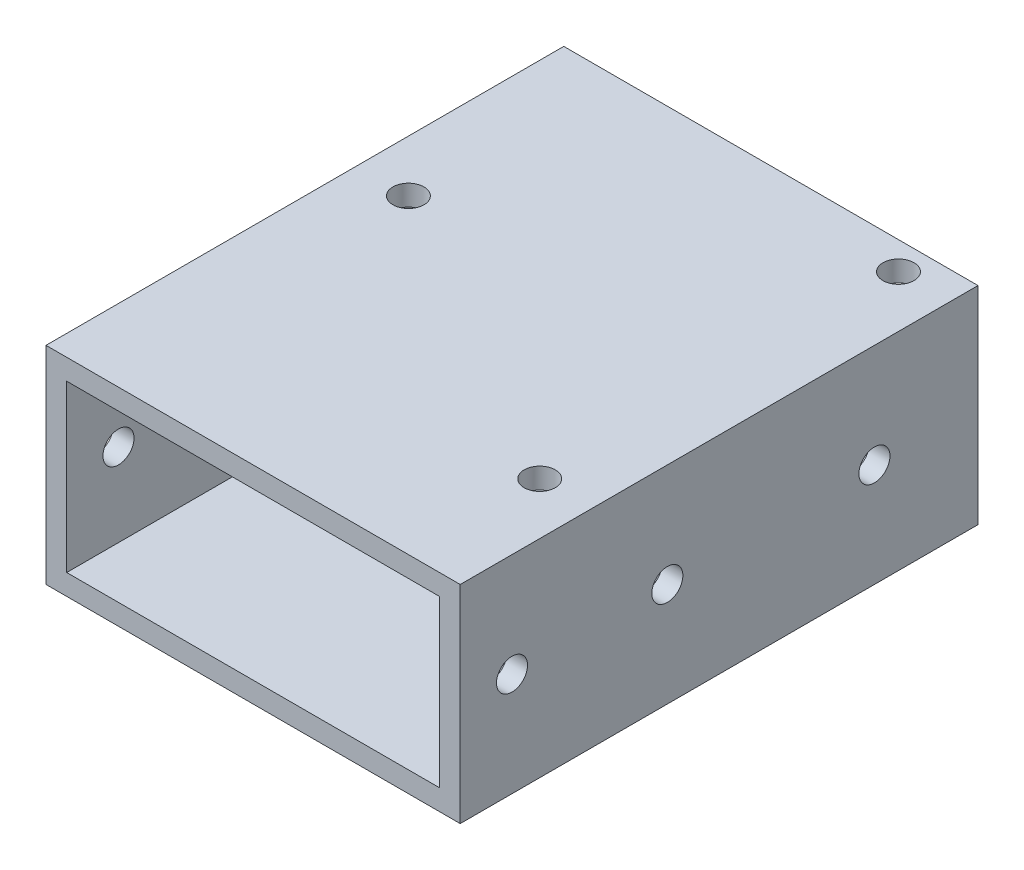
SolidWorks part; units mm, degrees
ref_plane "前视基准面" through (0, 0, 0) normal (0, 0, 1) x (1, 0, 0)
ref_plane "上视基准面" through (0, 0, 0) normal (0, 1, 0) x (1, 0, 0)
ref_plane "右视基准面" through (0, 0, 0) normal (1, 0, 0) x (0, 0, -1)
other "Configuration Table"
sketch "草图1" plane through (0, 0, 0) normal (0, 0, 1) x (1, 0, 0)
  line L1 (-20, 10) -> (20, 10)
  line L2 (-20, 10) -> (-20, -10)
  line L3 (-20, -10) -> (20, -10)
  line L4 (20, 10) -> (20, -10)
  line L5 (-20, 10) -> (20, -10) construction
  line L6 (-20, -10) -> (20, 10) construction
  line L7 (-18, 8) -> (18, 8)
  line L8 (-18, 8) -> (-18, -8)
  line L9 (-18, -8) -> (18, -8)
  line L10 (18, 8) -> (18, -8)
  line L11 (-18, 8) -> (18, -8) construction
  line L12 (-18, -8) -> (18, 8) construction
  point P0 (0, 0)
  point P6 (0, 0)
  dimension "D1" = 20
  dimension "D2" = 40
  dimension "D3" = 2
  dimension "D4" = 2
extrude "凸台-拉伸1" add sketch "草图1" along normal blind 50
sketch "草图2" plane through (0, 10, 0) normal (0, 1, 0) x (1, 0, 0)
  circle A0 centre (5, -20) radius 20 construction
  circle A1 centre (-15, -20) radius 1.5
  circle A2 centre (15, -2.6795) radius 1.5
  circle A3 centre (15, -37.3205) radius 1.5
  dimension "D1" = 40
  dimension "D2" = 3
  dimension "D3" = 3
  dimension "D4" = 3
  dimension "D5" = 120
  dimension "D6" = 5
  dimension "D7" = 20
extrude "切除-拉伸1" cut sketch "草图2" against normal blind 50
sketch "草图3" plane through (-20, 0, 0) normal (-1, 0, 0) x (0, 0, 1)
  line L0 (50, 10) -> (50, -10) construction
  circle A0 centre (10, 0) radius 1.5
  circle A1 centre (30, 0) radius 1.5
  circle A2 centre (45, 0) radius 1.5
  dimension "D1" = 3
  dimension "D2" = 3
  dimension "D3" = 3
  dimension "D4" = 5
  dimension "D5" = 15
  dimension "D6" = 20
extrude "切除-拉伸2" cut sketch "草图3" against normal blind 50
